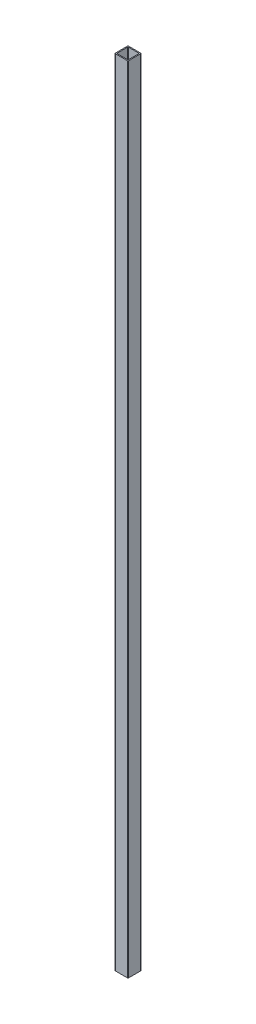
SolidWorks part; units mm, degrees
material "Hexcel AS4C (3000 Filaments)"
ref_plane "Front Plane" through (0, 0, 0) normal (0, 0, 1) x (1, 0, 0)
ref_plane "Top Plane" through (0, 0, 0) normal (0, 1, 0) x (1, 0, 0)
ref_plane "Right Plane" through (0, 0, 0) normal (1, 0, 0) x (0, 0, -1)
sketch "Sketch1" plane through (0, 0, 0) normal (0, 1, 0) x (1, 0, 0)
  line L1 (-9, -10) -> (9, -10)
  line L2 (-10, -9) -> (-10, 9)
  line L3 (-9, 10) -> (9, 10)
  line L4 (10, -9) -> (10, 9)
  line L5 (-10, -10) -> (10, 10) construction
  line L6 (-10, 10) -> (10, -10) construction
  line L7 (-7.5, -8.5) -> (7.5, -8.5)
  line L8 (-8.5, -7.5) -> (-8.5, 7.5)
  line L9 (-7.5, 8.5) -> (7.5, 8.5)
  line L10 (8.5, -7.5) -> (8.5, 7.5)
  line L11 (-8.5, -8.5) -> (8.5, 8.5) construction
  line L12 (-8.5, 8.5) -> (8.5, -8.5) construction
  arc A0 (-9, -10) -> (-10, -9) centre (-9, -9) cw
  arc A1 (9, 10) -> (10, 9) centre (9, 9) cw
  arc A2 (9, -10) -> (10, -9) centre (9, -9) ccw
  arc A3 (-10, 9) -> (-9, 10) centre (-9, 9) cw
  arc A4 (-7.5, -8.5) -> (-8.5, -7.5) centre (-7.5, -7.5) cw
  arc A5 (7.5, -8.5) -> (8.5, -7.5) centre (7.5, -7.5) ccw
  arc A6 (7.5, 8.5) -> (8.5, 7.5) centre (7.5, 7.5) cw
  arc A7 (-8.5, 7.5) -> (-7.5, 8.5) centre (-7.5, 7.5) cw
  point P0 (0, 0)
  point P18 (0, 0)
  dimension "D3" = 1
  dimension "D6" = 1
  dimension "D7" = 1
  dimension "D8" = 1
  dimension "D9" = 1
  dimension "D1" = 20
  dimension "D2" = 20
  dimension "D4" = 17
  dimension "D5" = 17
extrude "Boss-Extrude1" add sketch "Sketch1" along normal blind 1200
